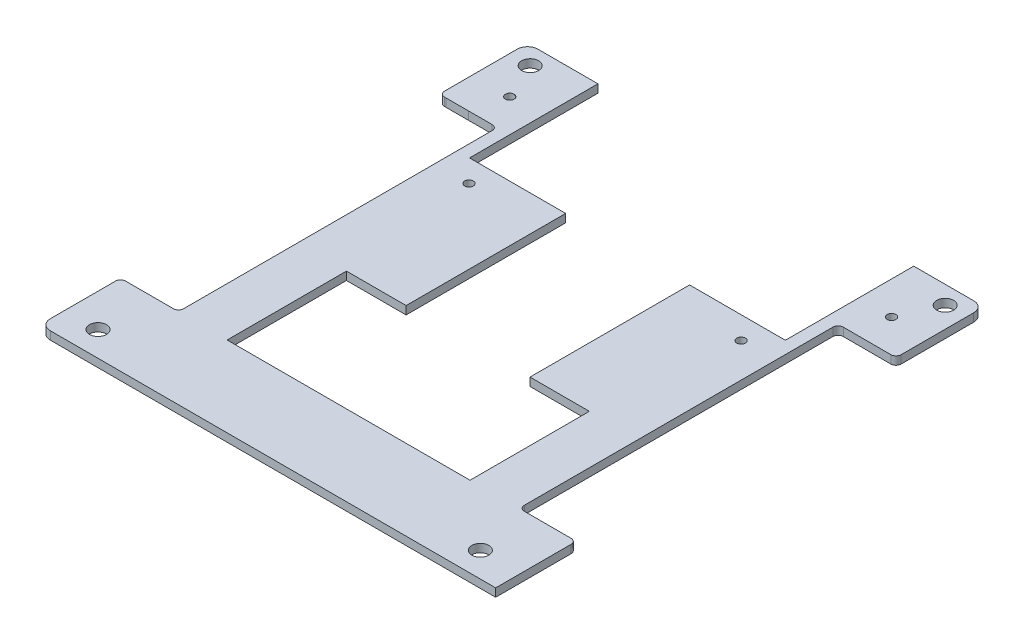
SolidWorks part; units mm, degrees
material "Copper"
ref_plane "Front Plane" through (0, 0, 0) normal (0, 0, 1) x (1, 0, 0)
ref_plane "Top Plane" through (0, 0, 0) normal (0, 1, 0) x (1, 0, 0)
ref_plane "Right Plane" through (0, 0, 0) normal (1, 0, 0) x (0, 0, -1)
sketch "Sketch1" plane through (0, 0, 0) normal (0, 1, 0) x (1, 0, 0)
  line L0 (-38.395, 30) -> (-42.73, 30)
  line L1 (-44, 31.27) -> (-44, 45)
  line L2 (42, 47) -> (30.435, 47)
  line L3 (44, 45) -> (44, 32)
  line L4 (44, 32) -> (44, 31.0156)
  line L5 (42.9984, 30.0156) -> (33.8256, 30.0304)
  line L6 (32.824, 29.0304) -> (32.824, -30.454)
  line L7 (-44, -38.977) -> (-44, -32.454)
  line L8 (-42, -47) -> (43.8497, -47)
  line L9 (-44, -45) -> (-44, -38.977)
  line L10 (-43, -31.454) -> (-36.1, -31.454)
  line L11 (43.8497, -37) -> (43.8497, -32.454)
  line L12 (42.8497, -31.454) -> (36.1, -31.454)
  line L13 (23.409, -31.5) -> (-23.409, -31.5)
  line L14 (-11.909, -8.5) -> (-23.409, -8.5)
  line L15 (30.435, 22.2554) -> (11.9708, 22.2554)
  line L16 (-11.909, -8.5) -> (-11.909, 22.2554)
  line L17 (30.435, 47) -> (30.435, 22.2554)
  line L18 (11.9708, 22.2554) -> (11.9708, -8.5)
  line L19 (-23.409, -31.5) -> (-23.409, -8.5)
  line L20 (11.9708, -8.5) -> (23.409, -8.5)
  line L21 (-36.1, -31.454) -> (-33.824, -31.454)
  line L22 (-32.824, -30.454) -> (-32.824, 29.0115)
  line L23 (-33.8265, 30.0115) -> (-38.395, 30)
  line L24 (-42.73, 30) -> (-43.011, 30.0031)
  line L25 (-44, 31.003) -> (-44, 31.27)
  line L28 (43.8497, -47) -> (43.8497, -37)
  line L33 (33.824, -31.454) -> (36.1, -31.454)
  line L34 (-23.409, 13.2954) -> (-23.409, -31.5) construction
  line L35 (23.409, -31.5) -> (23.409, -8.5)
  line L41 (-42, 47) -> (-30.435, 47)
  line L42 (-30.435, 47) -> (-30.435, 22.2554)
  line L43 (-30.435, 22.2554) -> (-11.909, 22.2554)
  circle A0 centre (40, 43.5) radius 1.6383
  circle A1 centre (-40, 43.5) radius 1.6383
  circle A2 centre (-37.6, -42.2) radius 1.6383
  circle A3 centre (36.1, -42.2) radius 1.6383
  circle A4 centre (-36.785, 36.35) radius 0.8382
  arc A5 (-42, 47) -> (-44, 45) centre (-42, 45) ccw
  arc A6 (44, 45) -> (42, 47) centre (42, 45) ccw
  circle A7 centre (-26.22, 17.9319) radius 0.8382
  circle A8 centre (26.22, 17.9319) radius 0.8382
  arc A9 (-43.011, 30.0031) -> (-44, 31.003) centre (-43, 31.003) cw
  arc A10 (-32.824, 29.0115) -> (-33.8265, 30.0115) centre (-33.824, 29.0115) ccw
  arc A11 (-44, -45) -> (-42, -47) centre (-42, -45) ccw
  arc A12 (44, 31.0156) -> (42.9984, 30.0156) centre (43, 31.0156) cw
  circle A13 centre (36.785, 36.368) radius 0.8382
  arc A14 (33.8256, 30.0304) -> (32.824, 29.0304) centre (33.824, 29.0304) ccw
  arc A15 (43.8497, -32.454) -> (42.8497, -31.454) centre (42.8497, -32.454) ccw
  arc A16 (32.824, -30.454) -> (33.824, -31.454) centre (33.824, -30.454) ccw
  arc A17 (-33.824, -31.454) -> (-32.824, -30.454) centre (-33.824, -30.454) ccw
  arc A18 (-44, -32.454) -> (-43, -31.454) centre (-43, -32.454) cw
  point P37 (-44, 30.014)
  point P48 (-32.824, 30.014)
  point P61 (44, 30.014)
  point P80 (32.824, 30.032)
  point P95 (32.824, -31.454)
  point P98 (-32.824, -31.454)
  dimension "D1" = 1
  dimension "D2" = 73.7
  dimension "D3" = 85.7
  dimension "D4" = 80
  dimension "D5" = 85.7
extrude "Boss-Extrude1" add sketch "Sketch1" along normal blind 1.575
